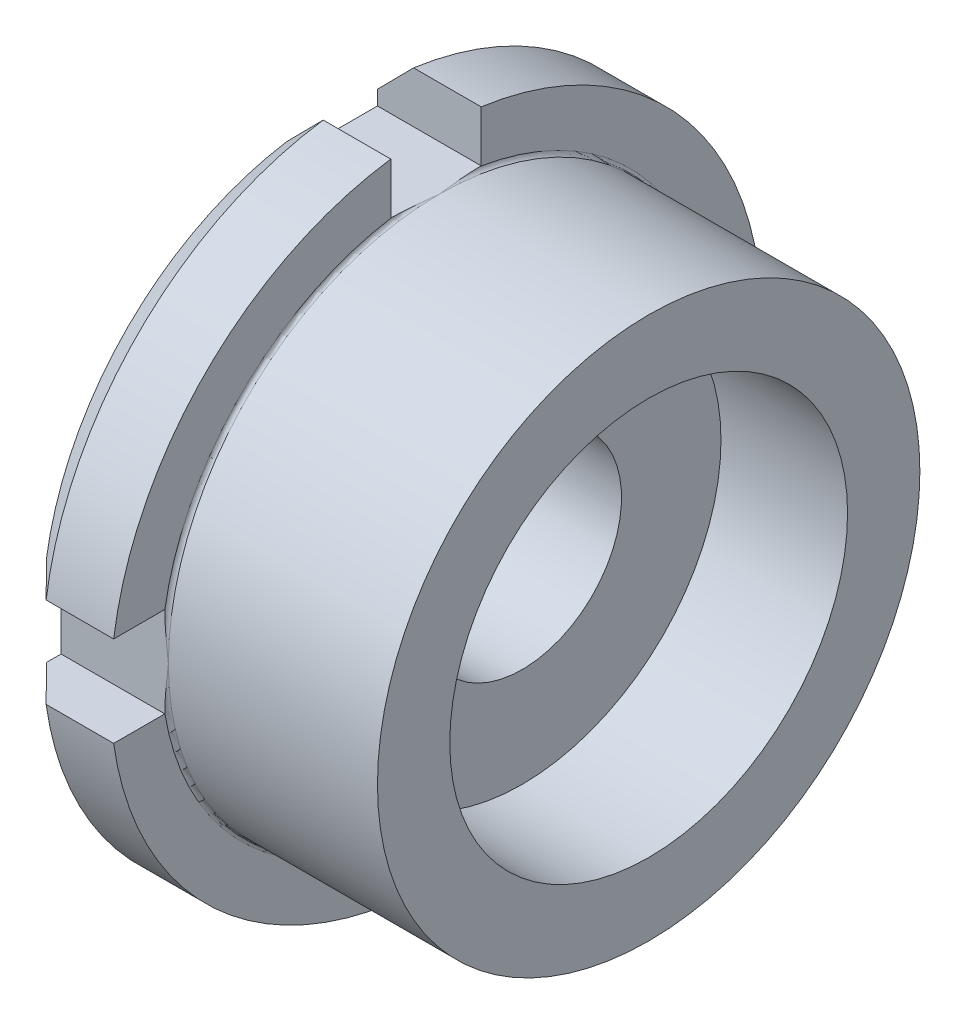
SolidWorks part; units mm, degrees
ref_plane "Front Plane" through (0, 0, 0) normal (0, 0, 1) x (1, 0, 0)
ref_plane "Top Plane" through (0, 0, 0) normal (0, 1, 0) x (1, 0, 0)
ref_plane "Right Plane" through (0, 0, 0) normal (1, 0, 0) x (0, 0, -1)
sketch "Sketch1" plane through (0, 0, 0) normal (0, 0, 1) x (1, 0, 0)
  line L0 (0, 0) -> (0, 5.5) construction
  line L1 (5.5, 5.5) -> (10.5, 5.5)
  line L2 (10.5, 5.5) -> (10.5, 11)
  line L3 (10.5, 11) -> (17.5, 11)
  line L4 (17.5, 11) -> (17.5, 15)
  line L5 (17.5, 15) -> (5.9357, 15)
  line L6 (5.7357, 15.2) -> (5.7357, 18)
  line L7 (5.7357, 18) -> (2, 18)
  line L8 (0, 16) -> (0, 12)
  line L9 (1, 11) -> (4.5, 11)
  line L10 (5.5, 10) -> (5.5, 5.5)
  line L11 (0, 16) -> (2, 18)
  line L12 (0, 0) -> (28.7428, 0) construction
  arc A0 (5.9357, 15) -> (5.7357, 15.2) centre (5.9357, 15.2) cw
  arc A1 (0, 12) -> (1, 11) centre (1, 12) ccw
  arc A2 (4.5, 11) -> (5.5, 10) centre (4.5, 10) cw
  point P19 (0, 11)
  point P22 (5.5, 11)
  dimension "D8" = 0.2
  dimension "D9" = 1
  dimension "D10" = 1
  dimension "D1" = 5.5
  dimension "D2" = 5.5
  dimension "D3" = 10.5
  dimension "D4" = 11
  dimension "D5" = 15
  dimension "D6" = 17.5
  dimension "D7" = 18
revolve "Revolve3" add sketch "Sketch1" angle 360 about L12
sketch "Sketch2" plane through (0, 0, 0) normal (-1, 0, 0) x (0, 0, 1)
  line L1 (2.5, 15) -> (2.5, 18)
  line L2 (-2.5, 15) -> (-2.5, 18)
  line L3 (-2.5, 15) -> (2.5, 15)
  line L7 (-2.5, 18) -> (2.5, 18)
  point P3 (2.5, 0)
  point P4 (2.5, 21.9264)
  point P5 (-2.5, 0)
  point P6 (-2.5, 21.9264)
  dimension "D1" = 5
  dimension "D2" = 3
extrude "Cut-Extrude1" cut sketch "Sketch2" against normal through all both and the other way through all
pattern_circular "CirPattern3" count 4 over 360 about axis through (0, 0, 0) along (1, 0, 0) of "Cut-Extrude1"
